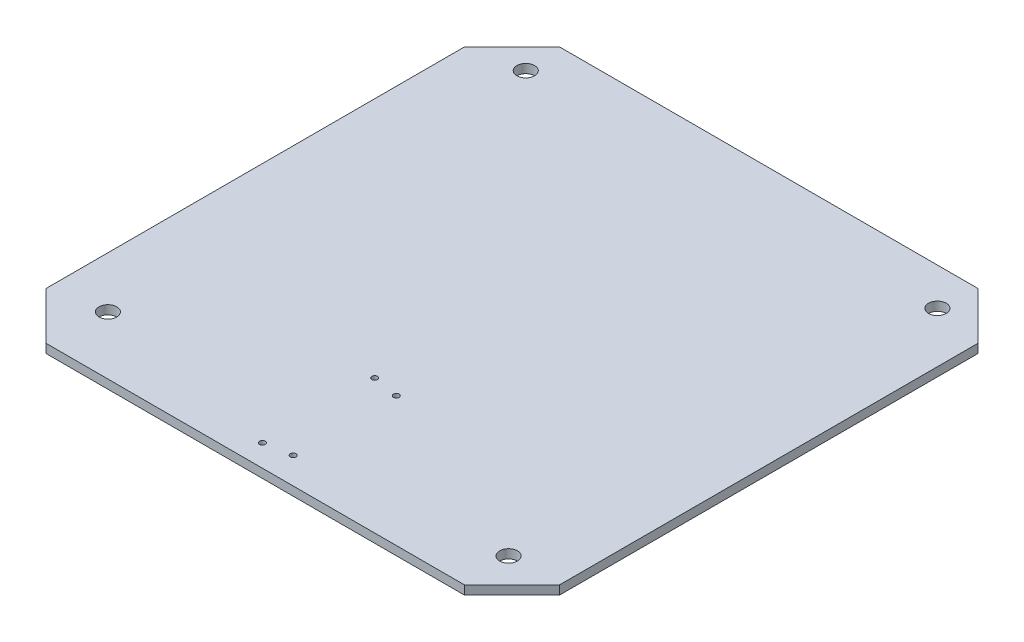
SolidWorks part; units mm, degrees
ref_plane "Front Plane" through (0, 0, 0) normal (0, 0, 1) x (1, 0, 0)
ref_plane "Top Plane" through (0, 0, 0) normal (0, 1, 0) x (1, 0, 0)
ref_plane "Right Plane" through (0, 0, 0) normal (1, 0, 0) x (0, 0, -1)
sketch "Sketch1" plane through (0, 0, 0) normal (0, 1, 0) x (1, 0, 0)
  line L1 (-46, -46) -> (46, -46)
  line L2 (-46, -46) -> (-46, 46)
  line L3 (-46, 46) -> (46, 46)
  line L4 (46, -46) -> (46, 46)
  line L5 (-46, -46) -> (46, 46) construction
  line L6 (-46, 46) -> (46, -46) construction
  circle A0 centre (-2.67, -21.93) radius 0.51
  circle A1 centre (2.03, -22.76) radius 0.51
  circle A2 centre (-2.67, -42.06) radius 0.51
  circle A3 centre (2.03, -41.24) radius 0.51
  point P0 (0, 0)
  point P14 (0, 0)
  point P15 (0, 0)
  point P16 (0, 0)
  dimension "D3" = 1.02
  dimension "D1" = 92
  dimension "D2" = 92
  dimension "D4" = 43.33
  dimension "D5" = 48.03
  dimension "D6" = 24.07
  dimension "D7" = 23.24
  dimension "D8" = 3.94
  dimension "D9" = 4.76
extrude "Boss-Extrude1" add sketch "Sketch1" along normal blind 1.59
chamfer "Chamfer1" distance 8.5 angle 45 4 edges at (46, 0.795, -46) (-46, 0.795, -46) (-46, 0.795, 46) (46, 0.795, 46)
hole_wizard "Ø1.0mm Dowel Hole1" positions "Sketch2" profile "Sketch3" hole size "Ø1.0" standard "ANSI Metric" end condition up to next
sketch "Sketch2" plane through (0, 1.59, 0) normal (0, 1, 0) x (1, 0, 0)
  point P0 (-36.8206, -35.5892)
  point P2 (36.9438, -37.5595)
  point P4 (36.9438, 39.2835)
  point P6 (-36.8206, 39.2835)
sketch "Sketch3" plane through (-36.8206, 1.59, 35.5892) normal (1, 0, 0) x (0, 0, 1)
  line L0 (0, 0) -> (0, 1.59)
  line L1 (0, 1.59) -> (1.59, 1.59)
  line L2 (1.59, 1.59) -> (1.59, 0)
  line L5 (1.59, 0) -> (0, 0)
  line L11 (0, -6.35) -> (0, 107.95) construction
  dimension "Thru Hole Dia." = 3.18
  dimension "Thru Hole Depth" = 1.59
